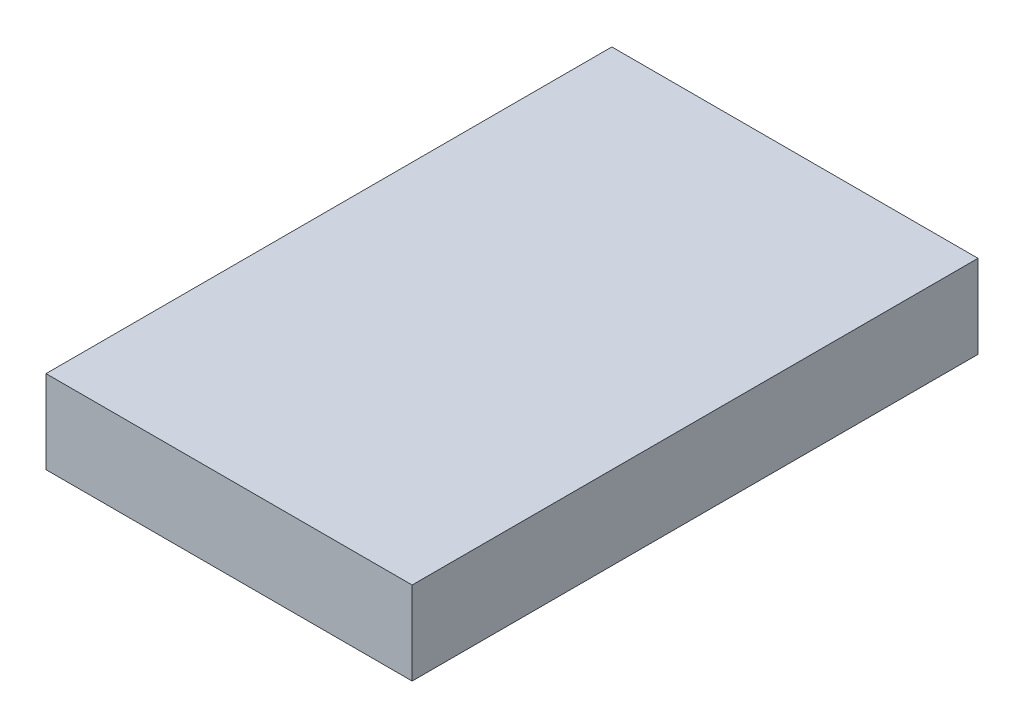
SolidWorks part; units mm, degrees
ref_plane "Front Plane" through (0, 0, 0) normal (0, 0, 1) x (1, 0, 0)
ref_plane "Top Plane" through (0, 0, 0) normal (0, 1, 0) x (1, 0, 0)
ref_plane "Right Plane" through (0, 0, 0) normal (1, 0, 0) x (0, 0, -1)
sketch "Sketch2" plane through (0, 0, 0) normal (0, 1, 0) x (1, 0, 0)
  line L1 (20.9566, 38.6882) -> (31.9566, 38.6882)
  line L2 (20.9566, 38.6882) -> (20.9566, 21.6882)
  line L3 (20.9566, 21.6882) -> (31.9566, 21.6882)
  line L4 (31.9566, 38.6882) -> (31.9566, 21.6882)
  dimension "D1" = 17
  dimension "D2" = 11
extrude "Boss-Extrude1" add sketch "Sketch2" along normal blind 2.5
